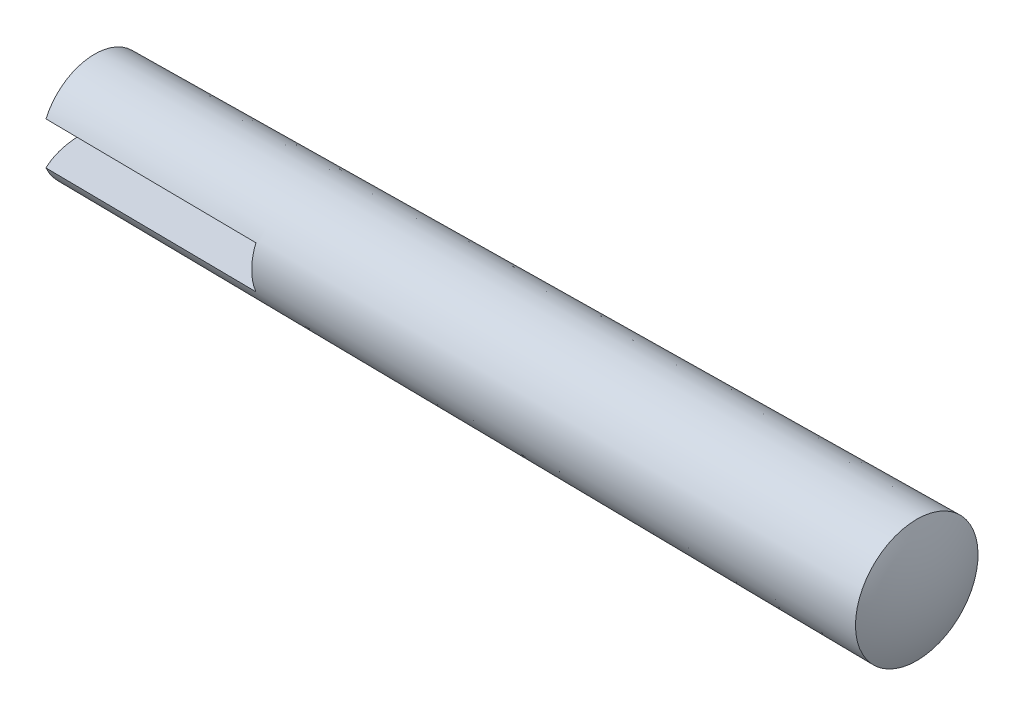
SolidWorks part; units mm, degrees
ref_plane "Plane1" through (0, 0, 0) normal (0, 0, 1) x (1, 0, 0)
ref_plane "Plane2" through (0, 0, 0) normal (0, 1, 0) x (1, 0, 0)
ref_plane "Plane3" through (0, 0, 0) normal (1, 0, 0) x (0, 0, -1)
sketch "Clipboard" plane through (0, 0, 0) normal (0, 0, 1) x (1, 0, 0)
  line L0 (0, 0) -> (10, 0)
  dimension "SplitDepth" = 10
ref_plane "SplitPlane" through (10.63, 0, 0) normal (1, 0, 0) x (0, 0, -1)
sketch "BodySke" plane through (0, 0, 0) normal (0, 0, 1) x (1, 0, 0)
  line L0 (0, 0) -> (210, 0) construction
  line L2 (0.63, 2.5) -> (39.37, 2.8874)
  line L4 (0, 0) -> (40, 0)
  line L5 (0.63, -2.5) -> (39.37, -2.8874) construction
  arc A0 (0.63, 2.5) -> (0, 0) centre (5.2753, 0) ccw
  arc A1 (39.37, 2.8874) -> (40, 0) centre (33.0683, 0) cw
  dimension "Diameter" = 5
  dimension "Length" = 40
  dimension "Crown_ht" = 0.63
  dimension "D1" = 0.63
  dimension "D2" = 0.573
revolve "Body" add sketch "BodySke" angle 360 about L0
sketch "SplSke" plane through (10.63, 0, 0) normal (1, 0, 0) x (0, 0, -1)
  line L0 (-20, 0) -> (20, 0) construction
  line L1 (0, 20) -> (0, -20) construction
  line L3 (-2.8874, -1) -> (2.8874, -1)
  line L4 (-2.8874, -1) -> (-2.8874, 1)
  line L5 (-2.8874, 1) -> (2.8874, 1)
  line L6 (2.8874, -1) -> (2.8874, 1)
  circle A0 centre (0, 0) radius 2.8874 construction
  dimension "Width" = 2
extrude "Split" cut sketch "SplSke" against normal through all
equation "\"D1@BodySke\" = \"Crown_ht@BodySke\""
equation "\"Offset@SplitPlane\" = \"SplitDepth@Clipboard\" + \"Crown_ht@BodySke\""
